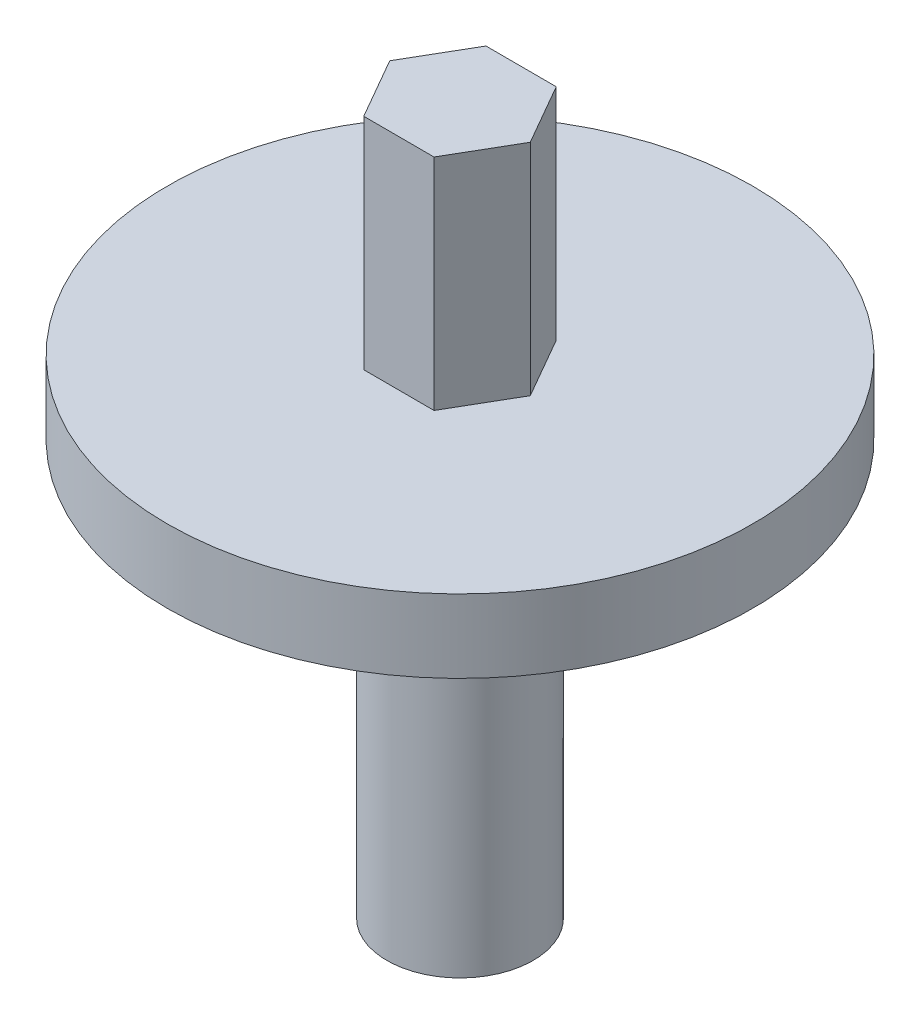
SolidWorks part; units mm, degrees
ref_plane "正面" through (0, 0, 0) normal (0, 0, 1) x (1, 0, 0)
ref_plane "平面" through (0, 0, 0) normal (0, 1, 0) x (1, 0, 0)
ref_plane "右側面" through (0, 0, 0) normal (1, 0, 0) x (0, 0, -1)
sketch "ｽｹｯﾁ1" plane through (0, 0, 0) normal (0, 0, 1) x (1, 0, 0)
  line L0 (0, 0) -> (27.5874, 0) construction
  line L1 (0, 0) -> (0, 31.9853) construction
  line L2 (0, 0) -> (0, 29)
  line L3 (0, 0) -> (3, 0)
  line L4 (3, 0) -> (3, 17)
  line L5 (3, 17) -> (12, 17)
  line L6 (12, 17) -> (12, 20)
  line L7 (12, 20) -> (3, 20)
  line L8 (3, 20) -> (3, 29)
  line L9 (3, 29) -> (0, 29)
  dimension "D1" = 29
  dimension "D2" = 3
  dimension "D3" = 17
  dimension "D4" = 9
  dimension "D5" = 3
  dimension "D6" = 9
revolve "回転1" add sketch "ｽｹｯﾁ1" angle 360 about L2
sketch "ｽｹｯﾁ2" plane through (0, 29, 0) normal (0, 1, 0) x (1, 0, 0)
  line L1 (1.438, -2.5031) -> (2.8867, -0.0062)
  line L2 (2.8867, -0.0062) -> (1.4488, 2.4969)
  line L3 (1.4488, 2.4969) -> (-1.438, 2.5031)
  line L4 (-1.438, 2.5031) -> (-2.8867, 0.0062)
  line L5 (-2.8867, 0.0062) -> (-1.4488, -2.4969)
  line L6 (-1.4488, -2.4969) -> (1.438, -2.5031)
  circle A0 centre (0, 0) radius 2.5 construction
  circle A2 centre (0, 0) radius 3
  dimension "D1" = 5
extrude "ｶｯﾄ - 押し出し2" cut sketch "ｽｹｯﾁ2" against normal blind 9
sketch "ｽｹｯﾁ4" plane through (0, 20, 0) normal (0, 1, 0) x (1, 0, 0)
  line L0 (0, 0) -> (0, 16.7525) construction
